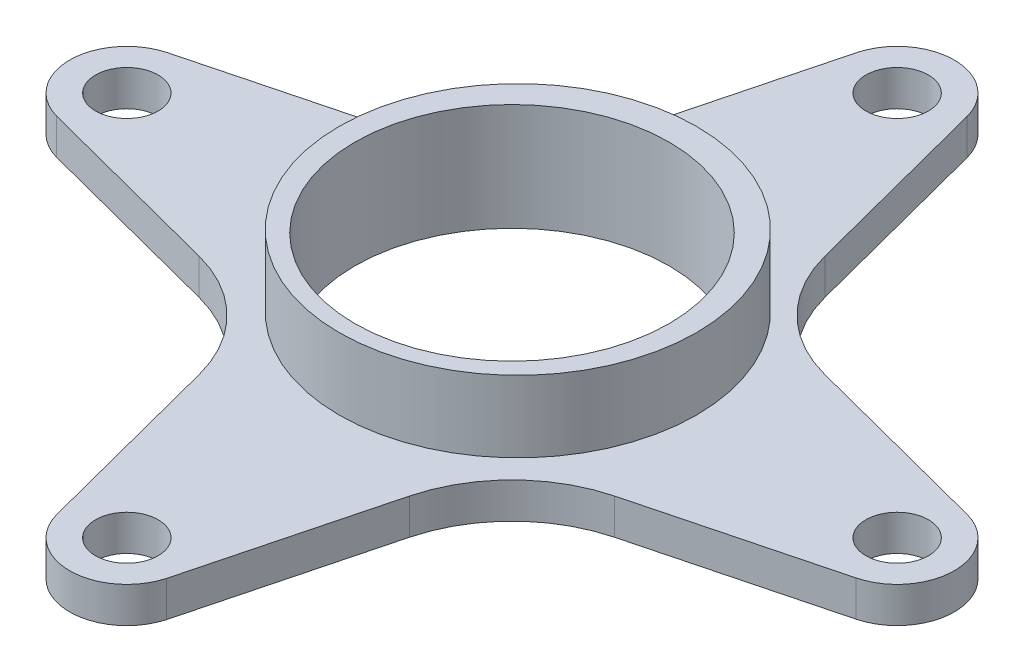
SolidWorks part; units mm, degrees
ref_plane "Front Plane" through (0, 0, 0) normal (0, 0, 1) x (1, 0, 0)
ref_plane "Top Plane" through (0, 0, 0) normal (0, 1, 0) x (1, 0, 0)
ref_plane "Right Plane" through (0, 0, 0) normal (1, 0, 0) x (0, 0, -1)
sketch "Sketch1" plane through (0, 0, 0) normal (0, 1, 0) x (1, 0, 0)
  line L0 (0, 68.4524) -> (0, 0) construction
  line L1 (0, 0) -> (37.992, 37.992) construction
  line L2 (0, 0) -> (-32.2088, 32.2088) construction
  line L3 (-18.6973, 36.8926) -> (-9.7793, 71.2077)
  line L4 (9.8335, 71.0075) -> (18.6979, 36.8928)
  line L5 (71.0075, -9.8335) -> (36.8928, -18.6979)
  line L6 (36.8926, 18.6973) -> (71.2077, 9.7793)
  line L7 (-9.8335, -71.0075) -> (-18.6979, -36.8928)
  line L8 (18.6973, -36.8926) -> (9.7793, -71.2077)
  line L9 (-71.0075, 9.8335) -> (-36.8928, 18.6979)
  line L10 (-36.8926, -18.6973) -> (-71.2077, -9.7793)
  circle A0 centre (0, 0) radius 31.75
  circle A1 centre (0, 68.4524) radius 5.5562
  circle A2 centre (0, 68.4524) radius 10.16
  circle A3 centre (68.4524, 0) radius 10.16
  circle A4 centre (68.4524, 0) radius 5.5563
  circle A5 centre (0, -68.4524) radius 10.16
  circle A6 centre (0, -68.4524) radius 5.5563
  circle A7 centre (-68.4524, 0) radius 10.16
  circle A8 centre (-68.4524, 0) radius 5.5563
  arc A9 (18.6979, 36.8928) -> (36.8926, 18.6973) centre (43.2816, 43.2807) ccw
  arc A10 (36.8928, -18.6979) -> (18.6973, -36.8926) centre (43.2807, -43.2816) ccw
  arc A11 (-18.6979, -36.8928) -> (-36.8926, -18.6973) centre (-43.2816, -43.2807) ccw
  arc A12 (-18.6973, 36.8926) -> (-36.8928, 18.6979) centre (-43.2807, 43.2816) cw
  circle A13 centre (0, 0) radius 27.94
  point P14 (22.4506, 22.4506)
  point P36 (0, 0)
  point P39 (-22.4506, 22.4506)
  dimension "D1" = 90
  dimension "D4" = 25.4
  dimension "D2" = 45
  dimension "D3" = 4
extrude "Boss-Extrude1" add sketch "Sketch1" along normal blind 6.35 contours A7 L10 A8 | L3 A12 L9 A7 L10 A11 L7 A5 L8 A10 L5 A3 L6 A9 L4 A2 A0 | L8 A5 A6 | A2 L3 A1 | A3 L6 A4 | A0 A13
sketch "Sketch2" plane through (0, 6.35, 0) normal (0, 1, 0) x (1, 0, 0)
  circle A0 centre (0, 0) radius 27.94
  circle A1 centre (0, 1.0384) radius 31.75
extrude "Boss-Extrude2" add sketch "Sketch2" along normal blind 12.7
